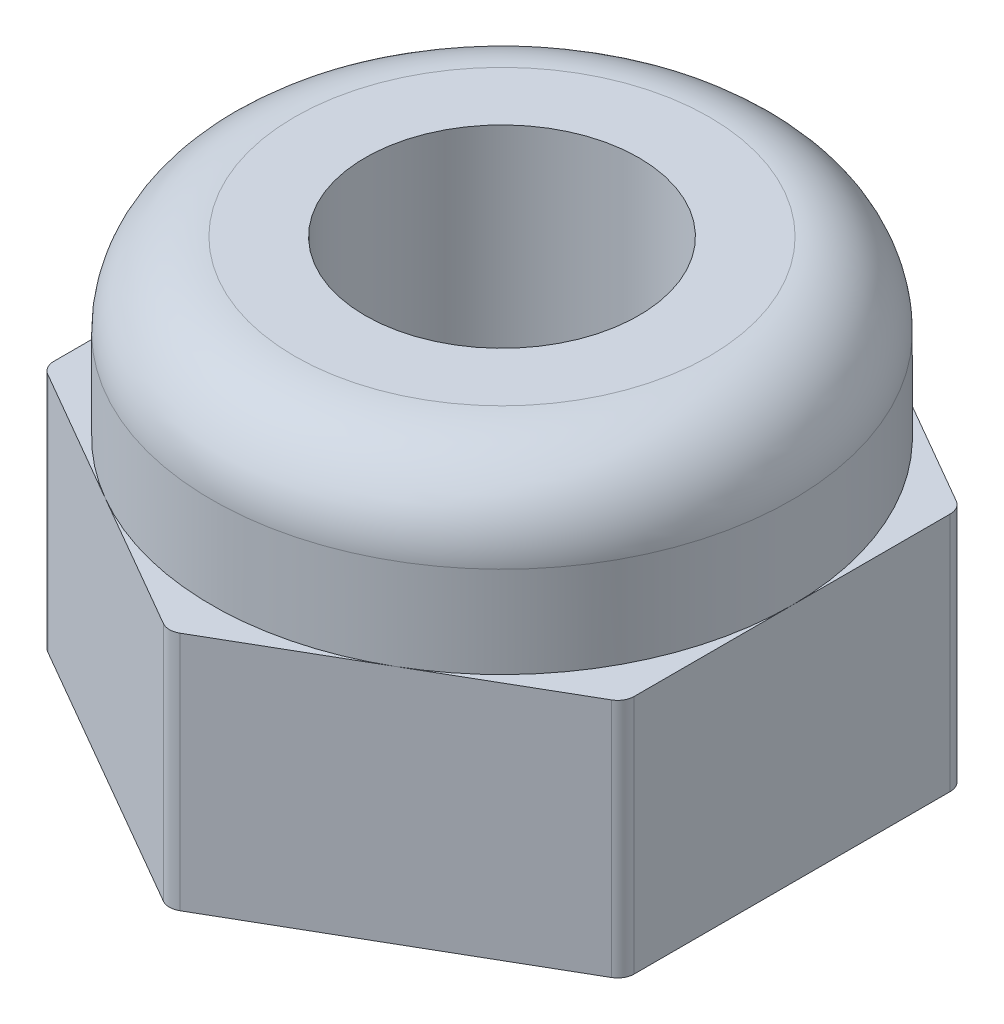
SolidWorks part; units mm, degrees
ref_plane "前视基准面" through (0, 0, 0) normal (0, 0, 1) x (1, 0, 0)
ref_plane "上视基准面" through (0, 0, 0) normal (0, 1, 0) x (1, 0, 0)
ref_plane "右视基准面" through (0, 0, 0) normal (1, 0, 0) x (0, 0, -1)
sketch "草图1" plane through (0, 0, 0) normal (0, 1, 0) x (1, 0, 0)
  line L1 (0, 4.0415) -> (-3.5, 2.0207)
  line L2 (-3.5, 2.0207) -> (-3.5, -2.0207)
  line L3 (-3.5, -2.0207) -> (0, -4.0415)
  line L4 (0, -4.0415) -> (3.5, -2.0207)
  line L5 (3.5, -2.0207) -> (3.5, 2.0207)
  line L6 (3.5, 2.0207) -> (0, 4.0415)
  circle A0 centre (0, 0) radius 3.5 construction
  dimension "D1" = 7
extrude "凸台-拉伸1" add sketch "草图1" along normal blind 2.9
sketch "草图2" plane through (0, 0, 0) normal (0, -1, 0) x (1, 0, 0)
  line L0 (3.5, 2.0207) -> (3.5, -2.0207) construction
  circle A0 centre (0, 0) radius 3.5
extrude "凸台-拉伸2" add sketch "草图2" against normal blind 5 contours A0
fillet "圆角1" radius 1 1 edges at (0, 5, -3.5)
fillet "圆角2" radius 0.2 6 edges at (-3.5, 1.45, 2.0207) (-3.5, 1.45, -2.0207) (0, 1.45, -4.0415) (3.5, 1.45, -2.0207) (3.5, 1.45, 2.0207) (0, 1.45, 4.0415)
hole_wizard "M4 螺纹孔1" positions "草图3" profile "草图4" tap size "M4" standard "ISO"
sketch "草图3" plane through (0, 0, 0) normal (0, -1, 0) x (-1, 0, 0)
  point P0 (0, 0)
sketch "草图4" plane through (0, 0, 0) normal (1, 0, 0) x (0, 0, -1)
  line L0 (0, 0) -> (0, 11.0914)
  line L1 (0, 11.0914) -> (1.65, 10.1)
  line L2 (1.65, 10.1) -> (1.65, 0)
  line L5 (1.65, 0) -> (0, 0)
  line L10 (0, 11.0914) -> (-1.65, 10.1) construction
  line L11 (0, -6.35) -> (0, 107.95) construction
  dimension "螺纹孔钻头直径" = 3.3
  dimension "螺纹孔钻头深度" = 10.1
  dimension "导头角度" = 118
cosmetic thread "孔螺蚊线1" parameters "D1"=8, "D2"=4
